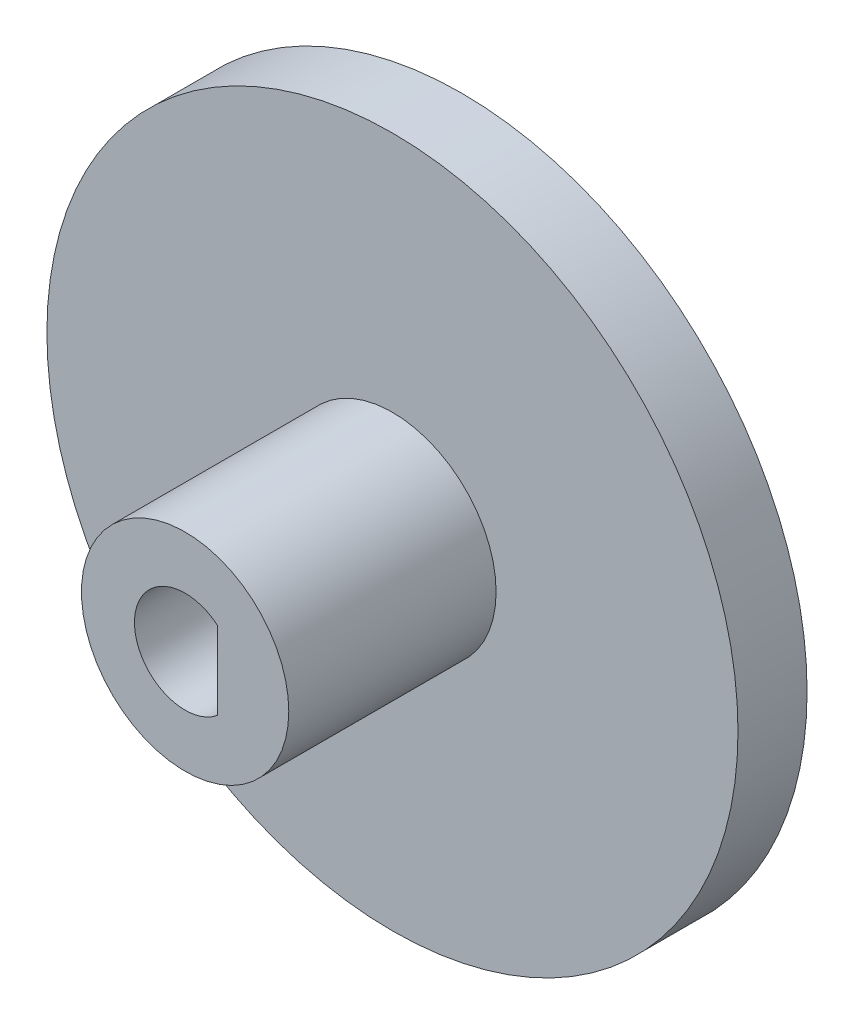
SolidWorks part; units mm, degrees
ref_plane "Спереди" through (0, 0, 0) normal (0, 0, 1) x (1, 0, 0)
ref_plane "Сверху" through (0, 0, 0) normal (0, 1, 0) x (1, 0, 0)
ref_plane "Справа" through (0, 0, 0) normal (1, 0, 0) x (0, 0, -1)
sketch "Эскиз1" plane through (0, 0, 0) normal (0, 0, 1) x (1, 0, 0)
  line L1 (1.4, 1.6971) -> (1.4, -1.6971)
  arc A0 (1.4, 1.6971) -> (1.4, -1.6971) centre (0, 0) ccw
  dimension "D1" = 2.2
  dimension "D2" = 1.4
sketch "Эскиз2" plane through (0, 0, 0) normal (0, 0, 1) x (1, 0, 0)
  circle A0 centre (0, 0) radius 4.5
  dimension "D1" = 9
sketch "Эскиз3" plane through (0, 0, 0) normal (0, 0, 1) x (1, 0, 0)
  circle A0 centre (0, 0) radius 15
  dimension "D1" = 30
extrude "Бобышка-Вытянуть1" add sketch "Эскиз2" along normal blind 9 contours A0
extrude "Бобышка-Вытянуть2" add sketch "Эскиз3" against normal blind 3 contours A0
extrude "Вырез-Вытянуть1" cut sketch "Эскиз1" along normal blind 10
